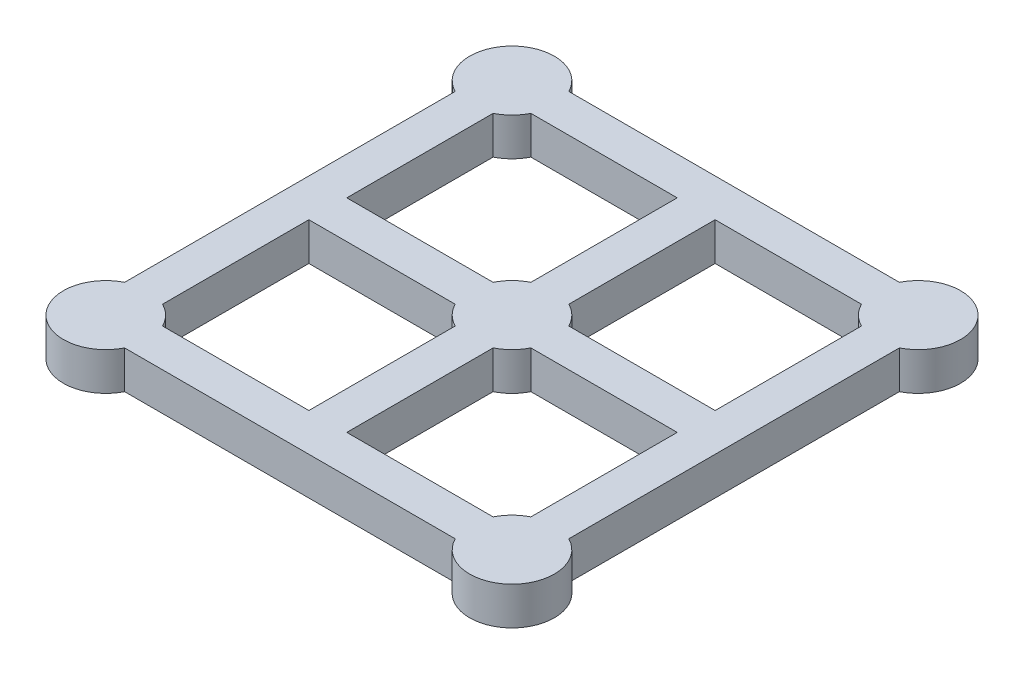
SolidWorks part; units mm, degrees
material "Plain Carbon Steel"
ref_plane "Front Plane" through (0, 0, 0) normal (0, 0, 1) x (1, 0, 0)
ref_plane "Top Plane" through (0, 0, 0) normal (0, 1, 0) x (1, 0, 0)
ref_plane "Right Plane" through (0, 0, 0) normal (1, 0, 0) x (0, 0, -1)
sketch "Sketch1" plane through (0, 0, 0) normal (0, 1, 0) x (1, 0, 0)
  point P0 (0, 0)
  line B0 (-23.7117, 270.2997) -> (-23.7117, -34.5003)
  line B1 (8.0383, -47.5738) -> (27.0535, -16.6183)
  line B2 (30.4276, 9.0677) -> (-0.9891, 114.4897)
  line B3 (36.899, -21.0938) -> (42.7449, -18.6145)
  line B4 (42.7449, -18.6145) -> (37.7887, -6.9257)
  line B5 (-9.8686, -40.9283) -> (-4.0226, -38.449)
  line B6 (-4.0226, -38.449) -> (-8.9788, -26.7603)
  line B7 (-15.8962, 7.3172) -> (-15.89, 20.0143)
  line B8 (-15.89, 20.0143) -> (-22.2395, 20.0156)
  line B9 (-22.2395, 20.0156) -> (-22.2456, 7.3186)
  line B10 (-14.8248, -29.2396) -> (-9.8686, -40.9283)
  arc B11 (-23.7117, -34.5003) -> (8.0383, -47.5738) centre (-5.1451, -34.5003) ccw
  arc B12 (27.0535, -16.6183) -> (30.4276, 9.0677) centre (0, 0) ccw
  ellipse B13 centre (71.3282, 7.2987) end of major axis (102.7639, 25.7116) minor radius 36.4199 (34.8998, 7.3064) -> (37.7887, -6.9257) ccw
  ellipse B14 centre (71.3282, 7.2987) end of major axis (34.4132, -14.3236) minor radius 42.7679 (28.5503, 7.3078) -> (31.9428, -9.405) ccw
  ellipse B15 centre (71.3282, 7.2987) end of major axis (146.5981, 51.3866) minor radius 87.204 (-15.8962, 7.3172) -> (-8.9788, -26.7603) ccw
  ellipse B16 centre (71.3282, 7.2987) end of major axis (152.0773, 54.596) minor radius 93.552 (-22.2456, 7.3186) -> (-14.8248, -29.2396) ccw
  ellipse B17 centre (16.3578, -29.6341) end of major axis (39.7425, -19.7187) minor radius 0.631 (39.7416, -19.7169) -> (-7.026, -39.5514) ccw
  ellipse B18 centre (6.2528, 20.1468) end of major axis (31.6528, 20.1344) minor radius 0.5489 (31.6508, 20.1414) -> (-19.1451, 20.1522) ccw
sketch_block_instance "Joint 2 Mounting Geometry-1"
sketch_block "Block1"
sketch "Sketch2" plane through (0, 0, 0) normal (0, 1, 0) x (1, 0, 0)
  line L0 (-15.5018, -17.272) -> (-1.778, -17.272)
  line L1 (-19.05, -19.05) -> (19.05, -19.05) construction
  line L7 (-19.05, -19.05) -> (-19.05, 19.05) construction
  line L8 (-19.05, 19.05) -> (19.05, 19.05) construction
  line L24 (19.05, -19.05) -> (19.05, 19.05) construction
  line L25 (-19.05, -19.05) -> (19.05, 19.05) construction
  line L26 (-19.05, 19.05) -> (19.05, -19.05) construction
  line L27 (15.5018, -20.828) -> (-15.5018, -20.828)
  line L28 (-17.272, -15.5018) -> (-17.272, -1.778)
  line L29 (-20.828, 15.5018) -> (-20.828, -15.5018)
  line L30 (-15.5018, 17.272) -> (-1.778, 17.272)
  line L31 (15.5018, 20.828) -> (-15.5018, 20.828)
  line L32 (20.828, 15.5018) -> (20.828, -15.5018)
  line L33 (17.272, -15.5018) -> (17.272, -1.778)
  line L34 (-1.778, 3.5482) -> (-1.778, 17.272)
  line L35 (1.778, 17.272) -> (1.778, 3.5482)
  line L36 (0, 0) -> (0, 20.828) construction
  line L37 (0, 0) -> (20.828, 0) construction
  line L38 (0, 0) -> (-20.828, 0) construction
  line L39 (0, 0) -> (0, -20.828) construction
  line L40 (3.5482, 1.778) -> (17.272, 1.778)
  line L41 (17.272, -1.778) -> (3.5482, -1.778)
  line L42 (1.778, -3.5482) -> (1.778, -17.272)
  line L43 (-1.778, -17.272) -> (-1.778, -3.5482)
  line L44 (-3.5482, -1.778) -> (-17.272, -1.778)
  line L45 (-17.272, 1.778) -> (-3.5482, 1.778)
  line L46 (1.778, 17.272) -> (15.5018, 17.272)
  line L47 (17.272, 1.778) -> (17.272, 15.5018)
  line L48 (-17.272, 1.778) -> (-17.272, 15.5018)
  line L49 (1.778, -17.272) -> (15.5018, -17.272)
  arc A0 (-17.272, 15.5018) -> (-15.5018, 17.272) centre (-19.05, 19.05) ccw
  arc A2 (15.5018, -20.828) -> (20.828, -15.5018) centre (19.05, -19.05) ccw
  arc A3 (-20.828, -15.5018) -> (-15.5018, -20.828) centre (-19.05, -19.05) ccw
  arc A4 (-1.778, 3.5482) -> (-3.5482, 1.778) centre (0, 0) ccw
  arc A5 (15.5018, 17.272) -> (17.272, 15.5018) centre (19.05, 19.05) ccw
  arc A6 (20.828, 15.5018) -> (15.5018, 20.828) centre (19.05, 19.05) ccw
  arc A7 (17.272, -15.5018) -> (15.5018, -17.272) centre (19.05, -19.05) ccw
  arc A8 (-15.5018, 20.828) -> (-20.828, 15.5018) centre (-19.05, 19.05) ccw
  arc A9 (-15.5018, -17.272) -> (-17.272, -15.5018) centre (-19.05, -19.05) ccw
  arc A10 (3.5482, 1.778) -> (1.778, 3.5482) centre (0, 0) ccw
  arc A11 (-3.5482, -1.778) -> (-1.778, -3.5482) centre (0, 0) ccw
  arc A12 (1.778, -3.5482) -> (3.5482, -1.778) centre (0, 0) ccw
  circle A13 centre (0, 0) radius 3.9688 construction
  point P0 (0, 0)
  dimension "D2" = 7.9375
  dimension "D1" = 38.1
  dimension "D3" = 3.556
  dimension "D4" = 3.556
  dimension "D5" = 3.556
  dimension "D6" = 3.556
  dimension "D7" = 3.556
  dimension "D8" = 3.556
extrude "Boss-Extrude1" add sketch "Sketch2" along normal blind 3.556
